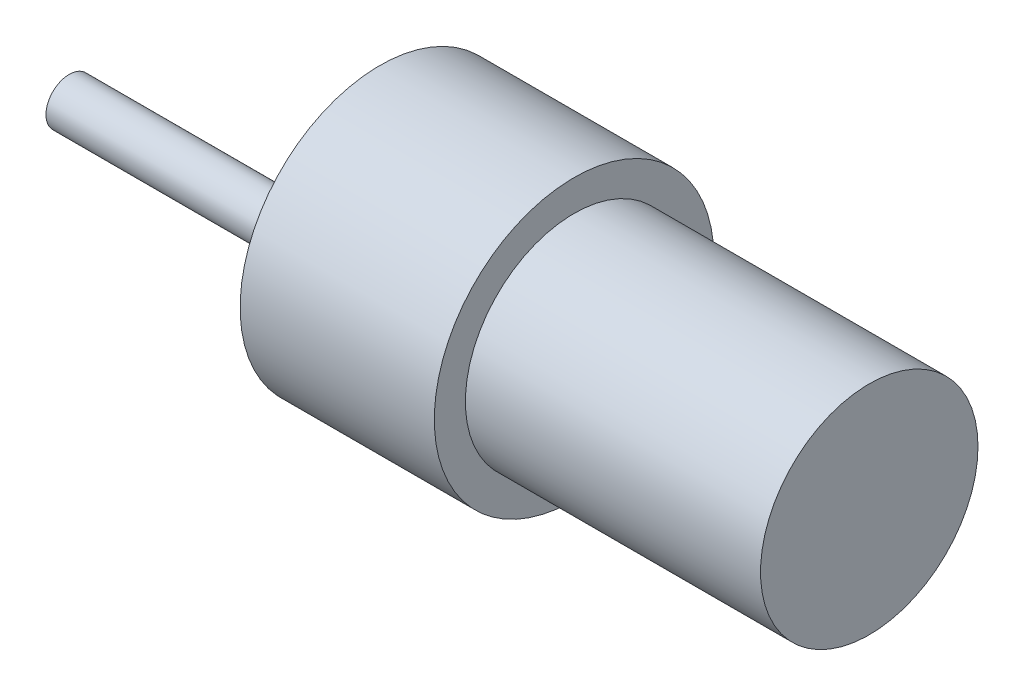
SolidWorks part; units mm, degrees
ref_plane "Front Plane" through (0, 0, 0) normal (0, 0, 1) x (1, 0, 0)
ref_plane "Top Plane" through (0, 0, 0) normal (0, 1, 0) x (1, 0, 0)
ref_plane "Right Plane" through (0, 0, 0) normal (1, 0, 0) x (0, 0, -1)
sketch "Sketch2" plane through (0, 0, 0) normal (0, 0, 1) x (1, 0, 0)
  line L0 (46.3931, 0) -> (46.3931, 18)
  line L1 (46.3931, 18) -> (71.3931, 18)
  line L2 (71.3931, 18) -> (71.3931, 14)
  line L3 (71.3931, 14) -> (109.3931, 14)
  line L4 (109.3931, 14) -> (109.3931, 0)
  line L5 (109.3931, 0) -> (46.3931, 0)
revolve "Revolve2" add sketch "Sketch2" angle 360 about L5
sketch "Sketch13" plane through (0, 0, 0) normal (0, 0, 1) x (1, 0, 0)
  line L0 (46.3931, -18) -> (46.3931, -6)
  line L1 (46.3931, 18) -> (46.3931, -18) construction
  line L2 (46.3931, -6) -> (19.8253, -6) construction
  line L3 (46.3931, -6) -> (46.3931, 0)
  line L4 (46.3931, 0) -> (36.3931, 0)
  line L5 (36.3931, 0) -> (36.3931, -3)
  line L6 (36.3931, -3) -> (6.3931, -3)
  line L7 (6.3931, -3) -> (6.3931, -6)
  line L8 (6.3931, -6) -> (46.3931, -6)
revolve "Revolve3" add sketch "Sketch13" angle 360 about L2
